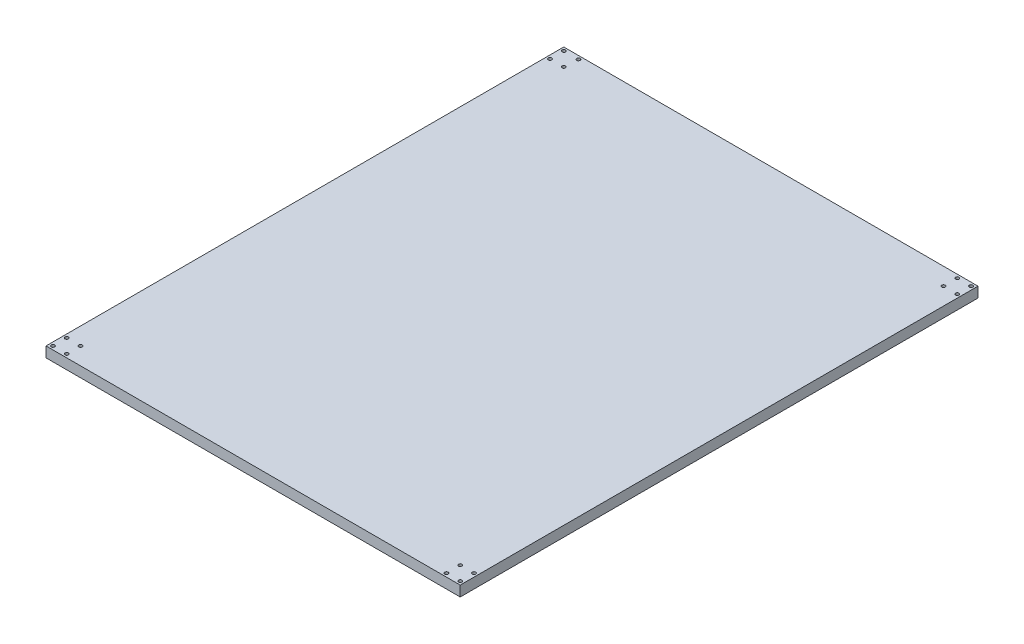
SolidWorks part; units mm, degrees
ref_plane "Front Plane" through (0, 0, 0) normal (0, 0, 1) x (1, 0, 0)
ref_plane "Top Plane" through (0, 0, 0) normal (0, 1, 0) x (1, 0, 0)
ref_plane "Right Plane" through (0, 0, 0) normal (1, 0, 0) x (0, 0, -1)
sketch "Sketch1" plane through (0, 0, 0) normal (0, 1, 0) x (1, 0, 0)
  line L1 (-4129.0233, 1607.601) -> (-4729.0233, 1607.601)
  line L2 (-4129.0233, 1607.601) -> (-4129.0233, 2357.601)
  line L3 (-4129.0233, 2357.601) -> (-4729.0233, 2357.601)
  line L4 (-4729.0233, 1607.601) -> (-4729.0233, 2357.601)
  dimension "D1" = 750
  dimension "D2" = 600
extrude "Boss-Extrude1" add sketch "Sketch1" along normal blind 15 contours L2 L3 L4 L1
hole_wizard "Ø5.0mm Dowel Hole1" positions "Sketch7" profile "Sketch8" hole size "Ø5.0" standard "ANSI Metric"
sketch "Sketch7" plane through (0, 15, 0) normal (0, 1, 0) x (1, 0, 0)
  line L0 (-4129.0233, 1607.601) -> (-4129.0233, 2357.601) construction
  line L1 (-4129.0233, 1607.601) -> (-4729.0233, 1607.601) construction
  point P0 (-4134.0233, 1632.601)
  point P2 (-4154.0233, 1632.601)
  point P4 (-4154.0233, 1612.601)
  point P6 (-4134.0233, 1612.601)
  point P16 (-4150.1037, 1610.4399)
  point P17 (0, 0)
  point P18 (0, 0)
  dimension "D1" = 5
  dimension "D2" = 5
  dimension "D3" = 5
  dimension "D4" = 25
  dimension "D5" = 5
  dimension "D6" = 25
  dimension "D7" = 25
  dimension "D8" = 25
sketch "Sketch8" plane through (-4134.0233, 15, -1632.601) normal (1, 0, 0) x (0, 0, 1)
  line L0 (0, 0) -> (0, 31.5022)
  line L1 (0, 31.5022) -> (2.5, 30)
  line L2 (2.5, 30) -> (2.5, 0)
  line L5 (2.5, 0) -> (0, 0)
  line L10 (0, 31.5022) -> (-2.5, 30) construction
  line L11 (0, -6.35) -> (0, 107.95) construction
  dimension "Hole Dia." = 5
  dimension "Hole Depth" = 30
  dimension "Drill Angle" = 118
hole_wizard "Ø5.0mm Dowel Hole2" positions "3DSketch2" profile "Sketch9" hole size "Ø5.0" standard "ANSI Metric" end condition through all
sketch3d "3DSketch2"
  line L0 (-4729.0233, 15, -1607.601) -> (-4729.0233, 15, -2357.601) construction
  line L1 (-4129.0233, 15, -2357.601) -> (-4729.0233, 15, -2357.601) construction
  line L2 (-4129.0233, 15, -1607.601) -> (-4129.0233, 15, -2357.601) construction
  line L3 (-4129.0233, 15, -1607.601) -> (-4729.0233, 15, -1607.601) construction
  point P0 (-4724.0233, 15, -2352.601)
  point P2 (-4702.8097, 15, -2352.601)
  point P4 (-4724.0233, 15, -2332.601)
  point P6 (-4704.0233, 15, -2332.601)
  point P8 (-4134.0233, 15, -2352.601)
  point P10 (-4154.0233, 15, -2352.601)
  point P12 (-4154.0233, 15, -2332.601)
  point P14 (-4134.0233, 15, -2332.601)
  point P16 (-4704.0233, 15, -1632.601)
  point P18 (-4704.0233, 15, -1612.601)
  point P20 (-4724.0233, 15, -1612.601)
  point P22 (-4724.0233, 15, -1632.601)
  point P29 (0, 0, 0)
  dimension "D1" = 5
  dimension "D2" = 5
  dimension "D3" = 5
  dimension "D4" = 5
  dimension "D5" = 25
  dimension "D6" = 25
  dimension "D7" = 25
  dimension "D8" = 5
  dimension "D9" = 5
  dimension "D10" = 5
  dimension "D11" = 25
  dimension "D12" = 5
  dimension "D13" = 25
  dimension "D14" = 25
  dimension "D15" = 25
  dimension "D16" = 5
  dimension "D17" = 5
  dimension "D18" = 5
  dimension "D19" = 5
  dimension "D20" = 25
  dimension "D21" = 25
  dimension "D22" = 25
  dimension "D23" = 25
sketch "Sketch9" plane through (-4724.0233, 15, -2352.601) normal (1, 0, 0) x (0, 0, 1)
  line L0 (0, 0) -> (0, 15)
  line L1 (0, 15) -> (2.5, 15)
  line L2 (2.5, 15) -> (2.5, 0)
  line L5 (2.5, 0) -> (0, 0)
  line L11 (0, -6.35) -> (0, 107.95) construction
  dimension "Thru Hole Dia." = 5
  dimension "Thru Hole Depth" = 15
